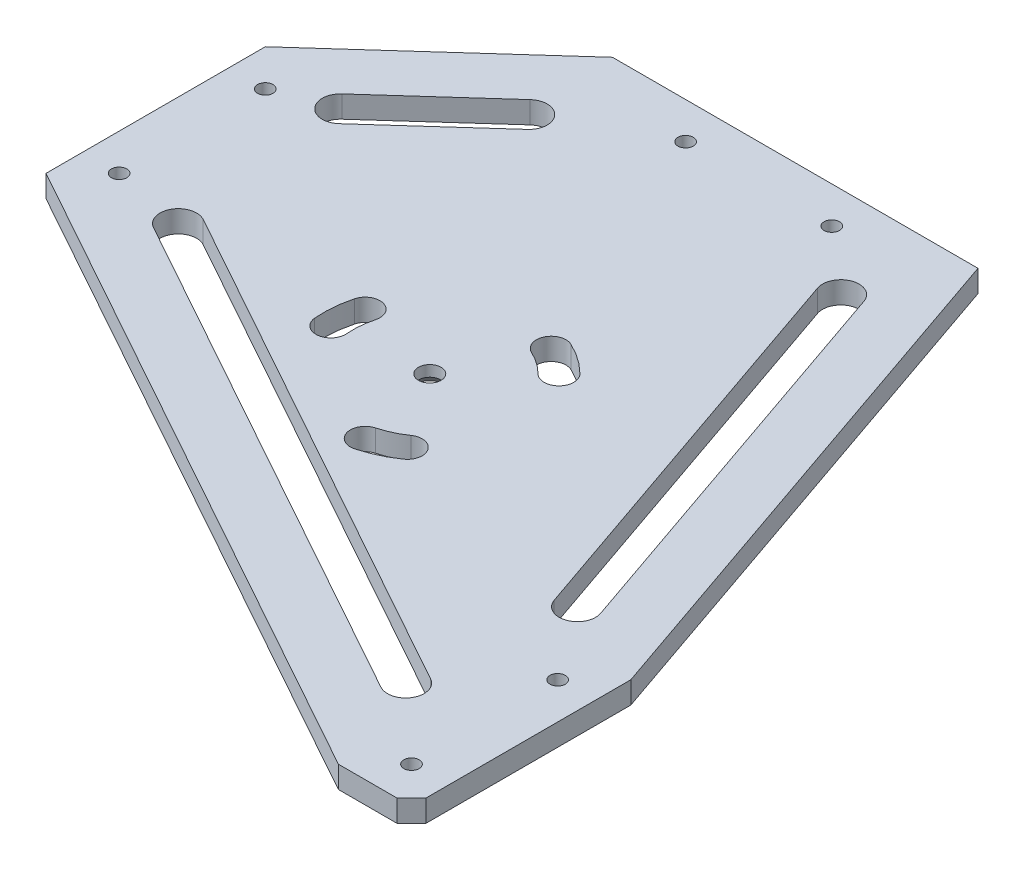
SolidWorks part; units mm, degrees
ref_plane "前视基准面" through (0, 0, 0) normal (0, 0, 1) x (1, 0, 0)
ref_plane "上视基准面" through (0, 0, 0) normal (0, 1, 0) x (1, 0, 0)
ref_plane "右视基准面" through (0, 0, 0) normal (1, 0, 0) x (0, 0, -1)
sketch "草图1" plane through (0, 0, 0) normal (0, 1, 0) x (1, 0, 0)
  line L0 (-50, 100) -> (50, 100)
  line L1 (50, 100) -> (100, -45)
  line L2 (100, -45) -> (100, -105)
  line L3 (100, -105) -> (-100, -5) construction
  line L4 (-100, -5) -> (-100, 55)
  line L5 (-100, 55) -> (-50, 100)
  line L6 (0, 100) -> (0, -55) construction
  line L7 (-90, 45) -> (-90, 5) construction
  line L8 (100, -105) -> (80, -105)
  line L9 (80, -105) -> (-100, -5)
  line L10 (90, -55) -> (90, -95) construction
  circle A0 centre (0, 0) radius 3.1
  circle A1 centre (-20, 90) radius 2.1
  circle A3 centre (-90, 45) radius 2.1
  circle A4 centre (-90, 5) radius 2.1
  circle A7 centre (20, 90) radius 2.1
  circle A8 centre (90, -55) radius 2.1
  circle A9 centre (90, -95) radius 2.1
  point P9 (0, 100)
  dimension "D1" = 200
  dimension "D6" = 6.2
  dimension "D7" = 10
  dimension "D8" = 10
  dimension "D9" = 4.2
  dimension "D5" = 5
  dimension "D12" = 40
  dimension "D14" = 10
  dimension "D15" = 205
  dimension "D2" = 100
  dimension "D3" = 10
  dimension "D4" = 100
  dimension "D10" = 40
  dimension "D11" = 10
  dimension "D13" = 20
  dimension "D16" = 10
extrude "凸台-拉伸1" add sketch "草图1" along normal mid plane 6
chamfer "倒角1" distance 2 angle 45 6 edges at (90, -3, 97.1) (90, -3, 57.1) (-90, -3, -2.9) (-90, -3, -42.9) (-20, -3, -87.9) (20, -3, -92.1)
chamfer "倒角3" distance 4 angle 45 1 edges at (100, 0, 105)
sketch "草图2" plane through (0, 3, 0) normal (0, 1, 0) x (1, 0, 0)
  line L0 (-75, 50.5928) -> (-47.8808, 75) construction
  line L1 (-78.3448, 54.3092) -> (-51.2257, 78.7165)
  line L2 (-71.6552, 46.8763) -> (-44.536, 71.2835)
  line L3 (-50, 100) -> (-100, 55) construction
  line L5 (50, 100) -> (-50, 100) construction
  line L6 (75.3961, -35) -> (37.465, 75) construction
  line L7 (70.6692, -36.63) -> (32.7382, 73.37)
  line L8 (80.1229, -33.37) -> (42.1919, 76.63)
  line L9 (100, -45) -> (50, 100) construction
  line L10 (70, -76.5653) -> (-70, 1.2125) construction
  line L11 (67.5718, -80.9361) -> (-72.4282, -3.1583)
  line L12 (72.4282, -72.1945) -> (-67.5718, 5.5833)
  line L13 (-100, -5) -> (80, -105) construction
  arc A0 (-78.3448, 54.3092) -> (-71.6552, 46.8763) centre (-75, 50.5928) ccw
  arc A1 (-44.536, 71.2835) -> (-51.2257, 78.7165) centre (-47.8808, 75) ccw
  arc A2 (70.6692, -36.63) -> (80.1229, -33.37) centre (75.3961, -35) ccw
  arc A3 (42.1919, 76.63) -> (32.7382, 73.37) centre (37.465, 75) ccw
  circle A4 centre (-90, 5) radius 2.1 construction
  circle A5 centre (-90, 45) radius 2.1 construction
  arc A6 (67.5718, -80.9361) -> (72.4282, -72.1945) centre (70, -76.5653) ccw
  arc A7 (-67.5718, 5.5833) -> (-72.4282, -3.1583) centre (-70, 1.2125) ccw
  circle A12 centre (-20, 90) radius 2.1 construction
  circle A13 centre (90, -95) radius 2.1 construction
  point P2 (-61.4404, 62.7964)
  point P12 (56.4305, 20)
  point P28 (0, -37.6764)
  dimension "D3" = 5
  dimension "D6" = 25
  dimension "D7" = 10
  dimension "D4" = 15
  dimension "D8" = 20
  dimension "D10" = 20
  dimension "D11" = 15
  dimension "D2" = 15
  dimension "D5" = 15
  dimension "D9" = 15
extrude "切除-拉伸1" cut sketch "草图2" against normal through all
chamfer "倒角4" distance 3 angle 45 1 edges at (0, -3, 3.1)
sketch "草图3" plane through (0, -3, 0) normal (0, -1, 0) x (1, 0, 0)
  line L0 (17.6777, -17.6777) -> (0, 0) construction
  line L1 (50, -100) -> (-50, -100) construction
  arc A0 (17.6777, -17.6777) -> (10.5655, -22.6577) centre (0, 0) cw construction
  arc A1 (12.2771, -26.3282) -> (20.5415, -20.5415) centre (0, 0) ccw
  arc A2 (8.8539, -18.9871) -> (14.8139, -14.8139) centre (0, 0) ccw
  arc A3 (8.8539, -18.9871) -> (12.2771, -26.3282) centre (10.5655, -22.6577) ccw
  arc A4 (20.5415, -20.5415) -> (14.8139, -14.8139) centre (17.6777, -17.6777) ccw
  point P4 (14.3394, -20.4788)
  dimension "D1" = 45
  dimension "D3" = 25
  dimension "D4" = 4.05
  dimension "D2" = 20
extrude "切除-拉伸2" cut sketch "草图3" against normal through all
pattern_circular "阵列(圆周)1" count 3 over 360 about axis through (0, 0, 0) along (0, 1, 0) of "切除-拉伸2"
